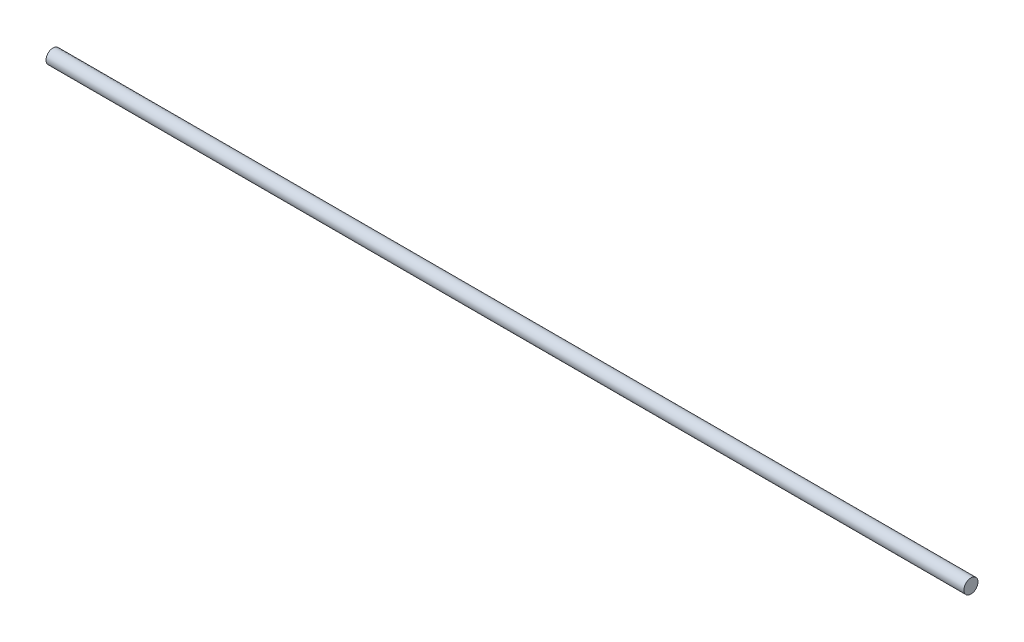
SolidWorks part; units mm, degrees
material "AISI 304"
ref_plane "前视基准面" through (0, 0, 0) normal (0, 0, 1) x (1, 0, 0)
ref_plane "上视基准面" through (0, 0, 0) normal (0, 1, 0) x (1, 0, 0)
ref_plane "右视基准面" through (0, 0, 0) normal (1, 0, 0) x (0, 0, -1)
sketch "草图1" plane through (0, 0, 0) normal (1, 0, 0) x (0, 0, -1)
  circle A0 centre (0, 0) radius 1
  dimension "D1" = 2
extrude "凸台-拉伸1" add sketch "草图1" along normal blind 130
